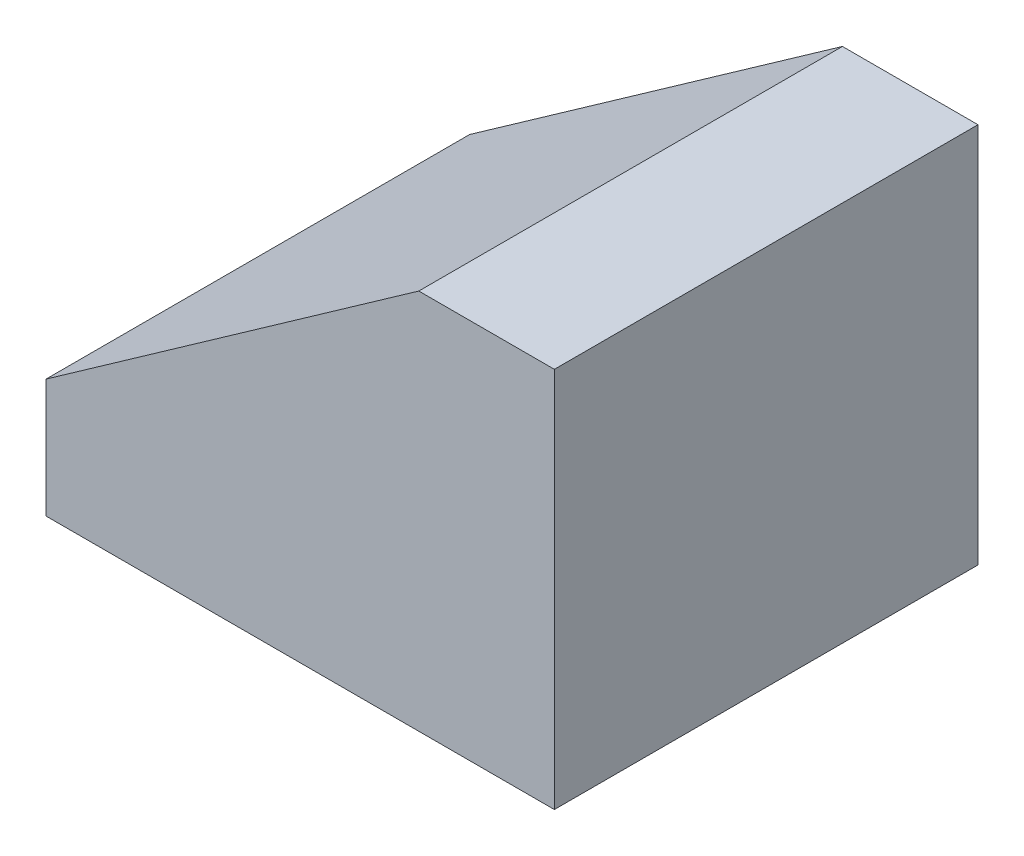
SolidWorks part; units mm, degrees
ref_plane "Plan de face" through (0, 0, 0) normal (0, 0, 1) x (1, 0, 0)
ref_plane "Plan de dessus" through (0, 0, 0) normal (0, 1, 0) x (1, 0, 0)
ref_plane "Plan de droite" through (0, 0, 0) normal (1, 0, 0) x (0, 0, -1)
sketch "Esquisse1" plane through (0, 0, 0) normal (0, 0, 1) x (1, 0, 0)
  line L0 (0, 0) -> (-120, 0)
  line L1 (-120, 0) -> (-120, 28)
  line L2 (-120, 28) -> (-32, 90)
  line L3 (-32, 90) -> (0, 90)
  line L4 (0, 90) -> (0, 0)
  dimension "D1" = 120
  dimension "D2" = 28
  dimension "D3" = 32
  dimension "D4" = 90
extrude "Boss.-Extru.1" add sketch "Esquisse1" along normal blind 100
